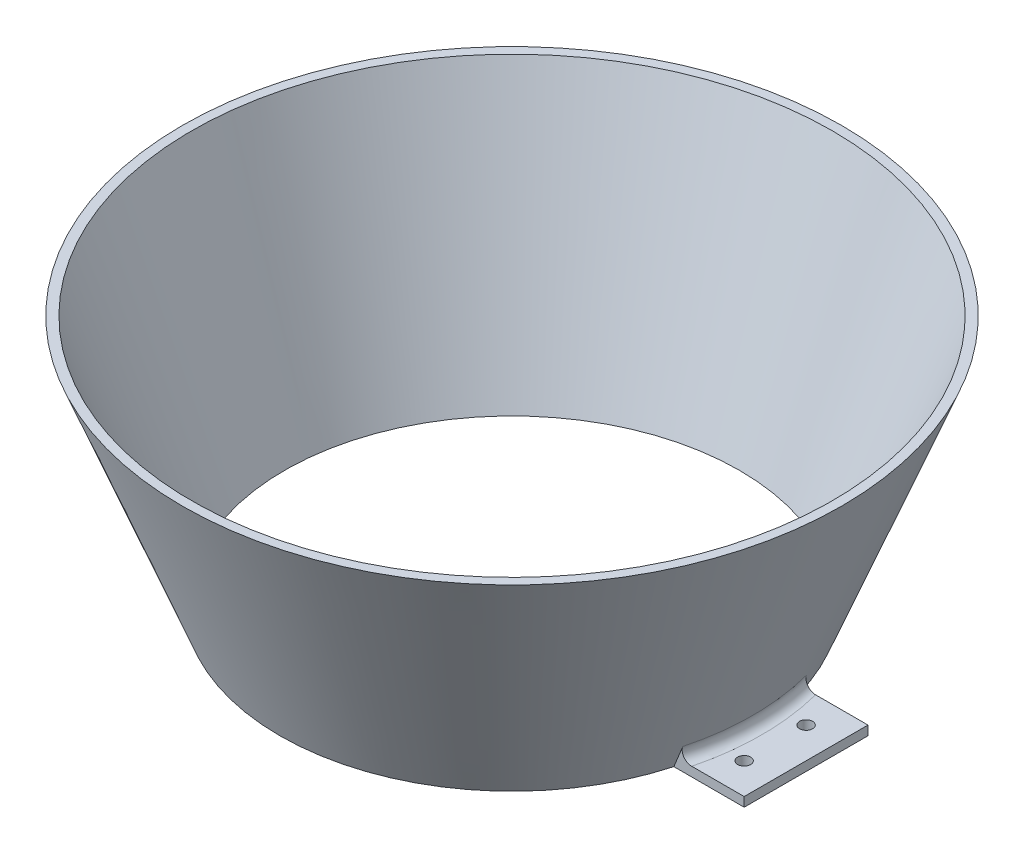
SolidWorks part; units mm, degrees
ref_plane "Front Plane" through (0, 0, 0) normal (0, 0, 1) x (1, 0, 0)
ref_plane "Top Plane" through (0, 0, 0) normal (0, 1, 0) x (1, 0, 0)
ref_plane "Right Plane" through (0, 0, 0) normal (1, 0, 0) x (0, 0, -1)
sketch "Sketch1" plane through (0, 0, 0) normal (0, 0, 1) x (1, 0, 0)
  line L0 (73.5, 0) -> (75, 0)
  line L1 (75, 0) -> (106.5, 80)
  line L2 (106.5, 80) -> (103.5, 80)
  line L3 (103.5, 80) -> (73.5, 0)
  line L4 (0, 0) -> (0, 73.1353) construction
  dimension "D1" = 1.5
  dimension "D2" = 73.5
  dimension "D3" = 3
  dimension "D4" = 80
  dimension "D5" = 30
revolve "Revolve1" add sketch "Sketch1" angle 360 about L4
sketch "Sketch2" plane through (0, 0, 0) normal (0, -1, 0) x (1, 0, 0)
  line L0 (72.2842, -20) -> (95, -20)
  line L1 (95, -20) -> (95, 20)
  line L2 (95, 20) -> (72.2842, 20)
  line L3 (0, 30.5442) -> (0, -50.5004) construction
  line L4 (-95, 20) -> (-72.2842, 20)
  line L5 (-95, -20) -> (-95, 20)
  line L6 (-72.2842, -20) -> (-95, -20)
  arc A0 (72.2842, 20) -> (72.2842, -20) centre (0, 0) cw
  circle A1 centre (0, 0) radius 75 construction
  arc A3 (-72.2842, 20) -> (-72.2842, -20) centre (0, 0) ccw
  dimension "D1" = 40
  dimension "D2" = 20
  dimension "D3" = 95
extrude "Boss-Extrude1" add sketch "Sketch2" against normal blind 3
sketch "Sketch3" plane through (0, 0, 0) normal (0, -1, 0) x (1, 0, 0)
  line L0 (-27.924, 0) -> (44.9048, 0) construction
  line L1 (0, 29.7164) -> (0, -26.1316) construction
  circle A0 centre (85, 10) radius 2.1
  circle A1 centre (85, -10) radius 2.1
  circle A2 centre (-85, -10) radius 2.1
  circle A3 centre (-85, 10) radius 2.1
  dimension "D1" = 4.2
  dimension "D2" = 85
  dimension "D3" = 10
extrude "Cut-Extrude1" cut sketch "Sketch3" against normal blind 3
fillet "Fillet1" radius 3 2 edges at (-76.1812, 3, 0) (76.1812, 3, 0)
